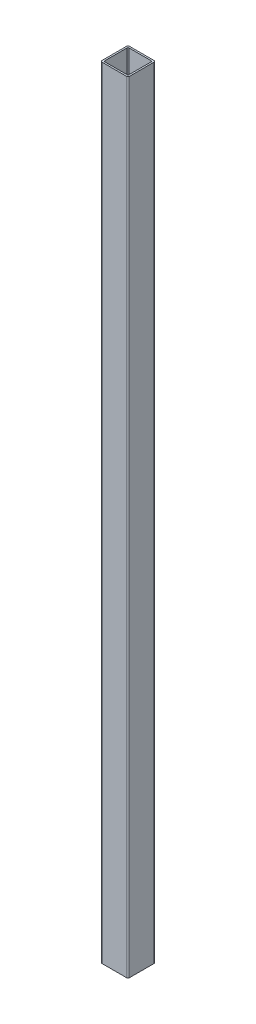
SolidWorks part; units mm, degrees
material "СТ3КП"
ref_plane "Спереди" through (0, 0, 0) normal (0, 0, 1) x (1, 0, 0)
ref_plane "Сверху" through (0, 0, 0) normal (0, 1, 0) x (1, 0, 0)
ref_plane "Справа" through (0, 0, 0) normal (1, 0, 0) x (0, 0, -1)
sketch "Эскиз1" plane through (0, 0, 0) normal (0, 1, 0) x (1, 0, 0)
  line B0 (-44, 50) -> (44, 50)
  line B1 (-50, 44) -> (-50, -44)
  line B2 (-44, -50) -> (44, -50)
  line B3 (50, 44) -> (50, -44)
  line B4 (-40, 44) -> (40, 44)
  line B5 (-44, 40) -> (-44, -40)
  line B6 (-40, -44) -> (40, -44)
  line B7 (44, 40) -> (44, -40)
  arc B8 (-50, -44) -> (-44, -50) centre (-44, -44) ccw
  arc B9 (44, -50) -> (50, -44) centre (44, -44) ccw
  arc B10 (44, 50) -> (50, 44) centre (44, 44) cw
  arc B11 (-44, 50) -> (-50, 44) centre (-44, 44) ccw
  arc B12 (-44, -40) -> (-40, -44) centre (-40, -40) ccw
  arc B13 (40, -44) -> (44, -40) centre (40, -40) ccw
  arc B14 (40, 44) -> (44, 40) centre (40, 40) cw
  arc B15 (-40, 44) -> (-44, 40) centre (-40, 40) ccw
sketch_block_instance "Пр_тр_100х100х6-1"
sketch_block "Пр_тр_100х100х6" parameters "D3"=6, "D4"=4, "D1"=100, "D2"=6
extrude "Бобышка-Вытянуть1" add sketch "Эскиз1" along normal up to surface (2842.5369 mm away)
